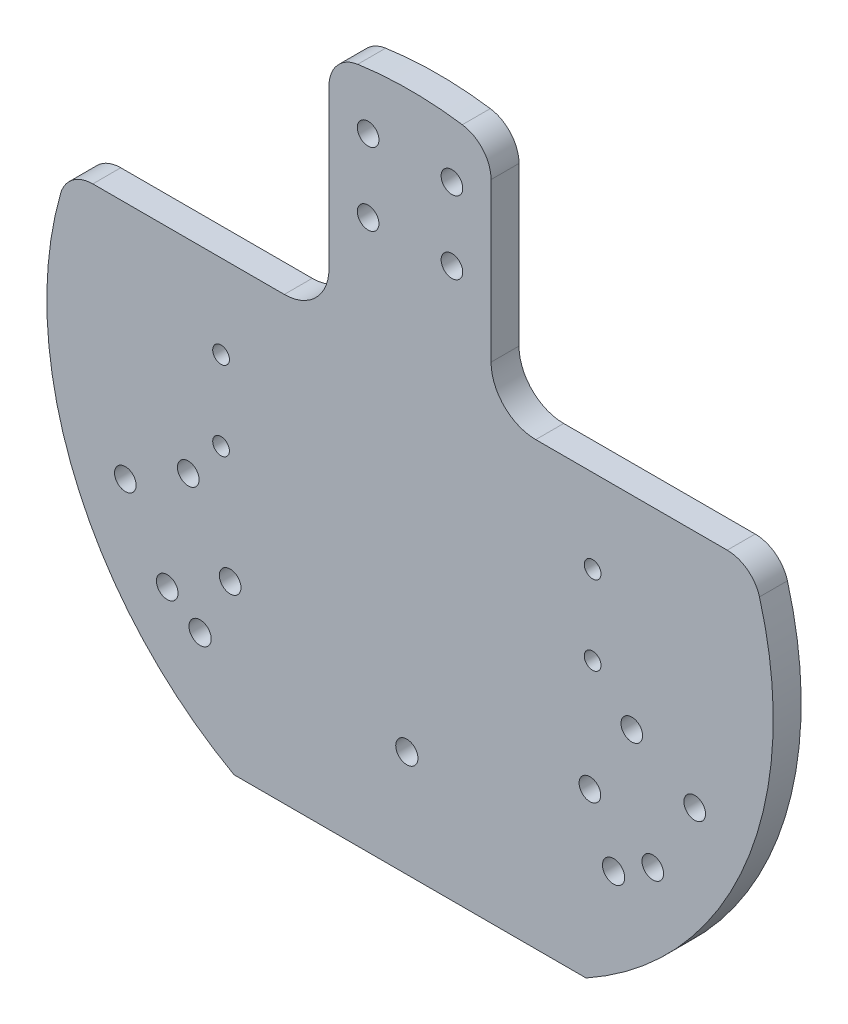
SolidWorks part; units mm, degrees
ref_plane "Front Plane" through (0, 0, 0) normal (0, 0, 1) x (1, 0, 0)
ref_plane "Top Plane" through (0, 0, 0) normal (0, 1, 0) x (1, 0, 0)
ref_plane "Right Plane" through (0, 0, 0) normal (1, 0, 0) x (0, 0, -1)
sketch "Sketch1" plane through (0, 0, 0) normal (0, 0, 1) x (1, 0, 0)
  circle A0 centre (0, 0) radius 82.55
  dimension "D1" = 165.1
extrude "Base" add sketch "Sketch1" along normal blind 6.35
sketch "Sketch2" [suppressed] plane through (0, 0, 0) normal (0, 0, 1) x (1, 0, 0)
  line L0 (0, 0) -> (-41.35, 0) construction
  line L1 (0, 3) -> (0, -3) construction
  circle A0 centre (-41.35, 0) radius 2.1
  circle A1 centre (41.35, 0) radius 2.1
  dimension "D2" = 4.2
  dimension "D1" = 41.35
sketch "Sketch3" plane through (0, 0, 0) normal (0, 0, 1) x (1, 0, 0)
  line L0 (0, 3) -> (0, -3) construction
  line L1 (0, -3) -> (0, 0) construction
  line L2 (0, 0) -> (-41.5, 0) construction
  line L3 (-41.5, -9) -> (-41.5, 9) construction
  circle A0 centre (-41.5, 9) radius 1.55
  circle A1 centre (-41.5, -9) radius 1.55
  circle A2 centre (41.5, -9) radius 1.55
  circle A3 centre (41.5, 9) radius 1.55
  dimension "D2" = 3.1
  dimension "D3" = 3.1
  dimension "D1" = 41.5
  dimension "D4" = 18
sketch "Sketch4" plane through (0, 0, 0) normal (0, 0, 1) x (1, 0, 0)
  line L0 (-85.6667, -23.1695) -> (-79.1121, -1.3046) construction
  line L1 (-79.1121, -1.3046) -> (-71.2848, 20.1376) construction
  line L2 (-71.2848, 20.1376) -> (-60.2213, 40.1036) construction
  line L3 (-60.2213, 40.1036) -> (-43.4112, 55.5456) construction
  line L4 (-43.4112, 55.5456) -> (-22.745, 65.2382) construction
  line L5 (-22.745, 65.2382) -> (0, 67.1622) construction
  line L6 (0, 0) -> (0, 67.1622) construction
  line L7 (43.4112, 55.5456) -> (22.745, 65.2382) construction
  line L8 (60.2213, 40.1036) -> (43.4112, 55.5456) construction
  line L9 (71.2848, 20.1376) -> (60.2213, 40.1036) construction
  line L10 (79.1121, -1.3046) -> (71.2848, 20.1376) construction
  line L11 (85.6667, -23.1695) -> (79.1121, -1.3046) construction
  circle A0 centre (-85.6667, -23.1695) radius 1.1305
  circle A1 centre (-79.1121, -1.3046) radius 1.1305
  circle A2 centre (-71.2848, 20.1376) radius 1.1305
  circle A3 centre (-60.2213, 40.1036) radius 1.1305
  circle A4 centre (-43.4112, 55.5456) radius 1.1305
  circle A5 centre (-22.745, 65.2382) radius 1.1305
  circle A6 centre (0, 67.1622) radius 1.1303
  circle A7 centre (22.745, 65.2382) radius 1.1305
  circle A8 centre (43.4112, 55.5456) radius 1.1305
  circle A9 centre (60.2213, 40.1036) radius 1.1305
  circle A10 centre (71.2848, 20.1376) radius 1.1305
  circle A11 centre (79.1121, -1.3046) radius 1.1305
  circle A12 centre (85.6667, -23.1695) radius 1.1305
  dimension "D3" = 2.261
  dimension "D5" = 2.2606
  dimension "D6" = 2.261
  dimension "D7" = 2.261
  dimension "D8" = 2.261
  dimension "D9" = 2.261
  dimension "D10" = 2.261
  dimension "D4" = 67.1622
extrude "Aesthetic Mounts" [suppressed] cut sketch "Sketch4" along normal through all
sketch "Sketch5" plane through (0, 0, 6.35) normal (0, 0, 1) x (1, 0, 0)
  line L0 (0, 0) -> (0, 23) construction
  circle A0 centre (0, 23) radius 1.55
  circle A1 centre (-17.91, 52.083) radius 1.55
  circle A2 centre (17.15, 52.083) radius 1.55
  dimension "D1" = 3.1
  dimension "D4" = 3.1
  dimension "D5" = 3.1
  dimension "D2" = 23
  dimension "D3" = 29.083
  dimension "D6" = 17.15
  dimension "D7" = 17.91
extrude "SenSkin Mounts, 4-40 through" [suppressed] cut sketch "Sketch5" against normal through all
hole_wizard "CSK for #6 Flat Head Machine Screw (100)1" positions "Sketch7" profile "Sketch6" countersink size "#6" standard "ANSI Inch" end condition through all
sketch "Sketch7" plane through (0, 0, 0) normal (0, 0, -1) x (-1, 0, 0)
  point P0 (-41.5, 9)
  point P3 (-41.5, -9)
  point P6 (42.95, 9)
  point P9 (42.95, -9)
sketch "Sketch6" plane through (41.5, 9, 0) normal (1, 0, 0) x (0, 1, 0)
  line L0 (0, 0) -> (0, 6.35)
  line L1 (0, 6.35) -> (1.8986, 6.35)
  line L2 (1.8986, 6.35) -> (1.8986, 1.38)
  line L3 (1.8986, 1.38) -> (3.5433, 0)
  line L5 (3.5433, 0) -> (0, 0)
  line L6 (-1.8986, 1.38) -> (-3.5433, 0) construction
  line L11 (0, -6.35) -> (0, 107.95) construction
  dimension "Thru Hole Dia." = 3.7973
  dimension "Thru Hole Depth" = 6.35
  dimension "Near C'Sink Dia." = 7.0866
  dimension "Near C'Sink Angle" = 100
sketch "Sketch8" plane through (0, 0, 0) normal (0, 0, -1) x (-1, 0, 0)
  line L0 (-40, -72.2115) -> (40, -72.2115)
  circle A0 centre (0, 0) radius 82.55 construction
  circle A2 centre (0, 0) radius 82.55
  circle A3 centre (0, 0) radius 82.55
  circle M14 centre (0, 0) radius 82.55
  dimension "D1" = 80
  dimension "D2" = 0
extrude "Cut-Extrude1" cut sketch "Sketch8" against normal through all contours L0 M14
sketch "Sketch9" plane through (0, 0, 0) normal (0, 0, -1) x (-1, 0, 0)
  line L0 (-40, -72.2115) -> (40, -72.2115) construction
  line L1 (15, -72.2115) -> (59.5092, -72.2115)
  line L2 (15, -72.2115) -> (15, -57.2115)
  line L3 (15, -57.2115) -> (59.5092, -57.2115)
  line L4 (59.5092, -72.2115) -> (59.5092, -57.2115)
  arc A0 (40, -72.2115) -> (-40, -72.2115) centre (0, 0) ccw construction
  dimension "D1" = 15
  dimension "D2" = 25
extrude "Cut-Extrude2" [suppressed] cut sketch "Sketch9" against normal through all
sketch "Sketch10" plane through (0, 0, 0) normal (0, 0, -1) x (-1, 0, 0)
  line L3 (-40, -72.2115) -> (40, -72.2115)
  line L6 (-40, -72.2115) -> (40, -72.2115)
  arc A1 (40, -72.2115) -> (-40, -72.2115) centre (0, 0) ccw
  arc A2 (40, -72.2115) -> (-40, -72.2115) centre (0, 0) ccw
  dimension "D1" = 0
sketch "Sketch11" plane through (0, 0, 0) normal (0, 0, -1) x (-1, 0, 0)
  line L0 (67.8961, -34.8004) -> (64.0861, -41.3996) construction
  line L1 (65.9911, -38.1) -> (0, 0) construction
  line L2 (50.4064, -18.1036) -> (40.8814, -34.6014)
  line L3 (50.4064, -18.1036) -> (64.7044, -26.3586)
  line L4 (40.8814, -34.6014) -> (55.1794, -42.8564)
  line L5 (64.7044, -26.3586) -> (55.1794, -42.8564)
  line L6 (50.4064, -18.1036) -> (55.1794, -42.8564) construction
  line L7 (40.8814, -34.6014) -> (64.7044, -26.3586) construction
  point P6 (52.7929, -30.48)
  dimension "D1" = 7.62
  dimension "D2" = 19.05
  dimension "D3" = 15.24
  dimension "D4" = 16.51
hole_wizard "#10 (0.1935) Diameter Hole1" positions "Sketch13" profile "Sketch12" hole size "#10" standard "ANSI Inch"
sketch "Sketch13" plane through (0, 0, 0) normal (0, 0, -1) x (-1, 0, 0)
  point P0 (40.8814, -34.6014)
  point P3 (50.4064, -18.1036)
  point P6 (64.7044, -26.3586)
  point P9 (55.1794, -42.8564)
sketch "Sketch12" plane through (-40.8814, -34.6014, 0) normal (1, 0, 0) x (0, 1, 0)
  line L0 (0, 0) -> (0, 7.8266)
  line L1 (0, 7.8266) -> (2.4574, 6.35)
  line L2 (2.4574, 6.35) -> (2.4574, 0)
  line L5 (2.4574, 0) -> (0, 0)
  line L10 (0, 7.8266) -> (-2.4575, 6.35) construction
  line L11 (0, -6.35) -> (0, 107.95) construction
  dimension "Hole Dia." = 4.9149
  dimension "Hole Depth" = 6.35
  dimension "Drill Angle" = 118
pattern_circular "CirPattern1" count 3 over 360 about axis through (0, 0, 0) along (0, 0, 1) of "#10 (0.1935) Diameter Hole1"
sketch "Sketch14" plane through (0, 0, 6.35) normal (0, 0, 1) x (1, 0, 0)
  line L0 (0, 82.55) -> (0, -103.9796) construction
  line L1 (-28.575, 28.05) -> (-123.1944, 28.05)
  line L2 (-18.415, 38.21) -> (-18.415, 124.9214)
  line L3 (-18.415, 124.9214) -> (-123.1944, 124.9214)
  line L4 (-123.1944, 28.05) -> (-123.1944, 124.9214)
  line L5 (123.1944, 28.05) -> (123.1944, 124.9214)
  line L6 (18.415, 124.9214) -> (123.1944, 124.9214)
  line L7 (18.415, 38.21) -> (18.415, 124.9214)
  line L8 (28.575, 28.05) -> (123.1944, 28.05)
  circle A0 centre (-41.5, 9) radius 1.55 construction
  circle A1 centre (-9.525, 69.215) radius 2.4574 construction
  arc A2 (-28.575, 28.05) -> (-18.415, 38.21) centre (-28.575, 38.21) ccw
  arc A3 (40, -72.2115) -> (-40, -72.2115) centre (0, 0) ccw construction
  arc A4 (28.575, 28.05) -> (18.415, 38.21) centre (28.575, 38.21) cw
  dimension "D3" = 10.16
  dimension "D1" = 19.05
  dimension "D2" = 8.89
extrude "Cut-Extrude3" cut sketch "Sketch14" against normal through all
fillet "Fillet1" radius 7.62 4 edges at (77.6383, 28.05, 3.175) (-77.6383, 28.05, 3.175) (-18.415, 80.4698, 3.175) (18.415, 80.4698, 3.175)
hole_wizard "CSK for #6 Flat Head Machine Screw (100)2" [suppressed] positions "Sketch16" profile "Sketch15" countersink size "#6" standard "ANSI Inch"
sketch "Sketch16" plane through (0, 0, 6.35) normal (0, 0, 1) x (1, 0, 0)
  point P0 (-71.2848, 20.1376)
  point P3 (-79.1121, -1.3046)
  point P6 (71.2848, 20.1376)
  point P9 (79.1121, -1.3046)
sketch "Sketch15" plane through (-71.2848, 20.1376, 6.35) normal (1, 0, 0) x (0, -1, 0)
  line L0 (0, 0) -> (0, 6.35)
  line L1 (0, 6.35) -> (1.8986, 6.35)
  line L2 (1.8986, 6.35) -> (1.8986, 1.38)
  line L3 (1.8986, 1.38) -> (3.5433, 0)
  line L5 (3.5433, 0) -> (0, 0)
  line L6 (-1.8986, 1.38) -> (-3.5433, 0) construction
  line L11 (0, -6.35) -> (0, 107.95) construction
  dimension "Thru Hole Dia." = 3.7973
  dimension "Thru Hole Depth" = 6.35
  dimension "Near C'Sink Dia." = 7.0866
  dimension "Near C'Sink Angle" = 100
hole_wizard "#8 (0.199) Diameter Hole1" positions "Sketch18" profile "Sketch17" hole size "#8" standard "ANSI Inch" end condition through all
sketch "Sketch18" plane through (0, 0, 0) normal (0, 0, -1) x (-1, 0, 0)
  point P0 (47.715, -48.0815)
  point P3 (0.725, -48.0815)
  point P6 (-46.265, -48.0815)
sketch "Sketch17" plane through (-47.715, -48.0815, 0) normal (1, 0, 0) x (0, 1, 0)
  line L0 (0, 0) -> (0, 6.35)
  line L1 (0, 6.35) -> (2.5273, 6.35)
  line L2 (2.5273, 6.35) -> (2.5273, 0)
  line L5 (2.5273, 0) -> (0, 0)
  line L11 (0, -6.35) -> (0, 107.95) construction
  dimension "Thru Hole Dia." = 5.0546
  dimension "Thru Hole Depth" = 6.35
